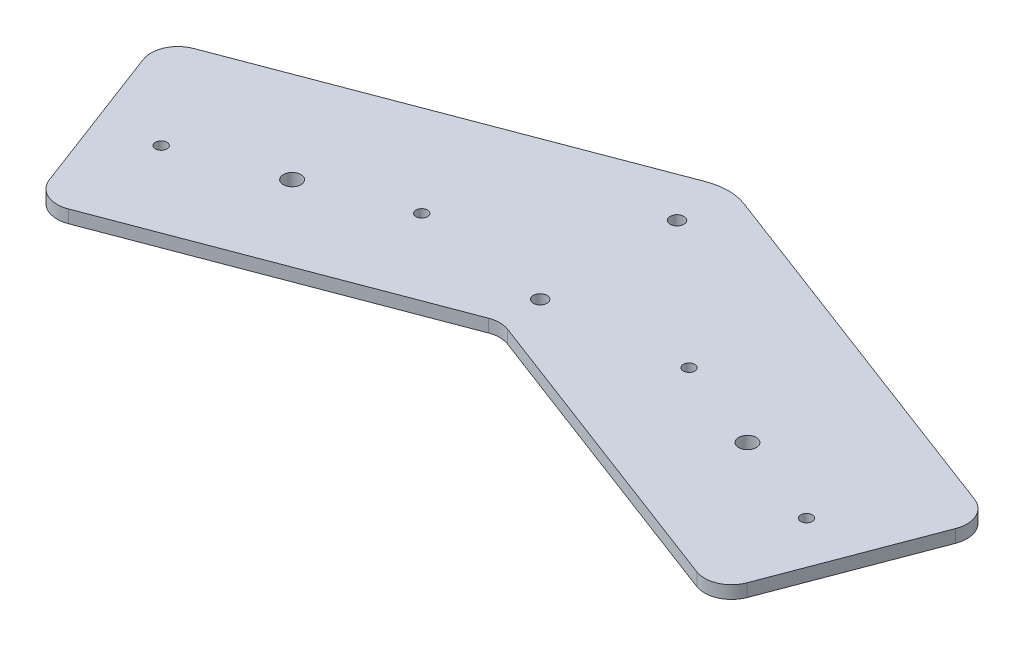
SolidWorks part; units mm, degrees
ref_plane "Front Plane" through (0, 0, 0) normal (0, 0, 1) x (1, 0, 0)
ref_plane "Top Plane" through (0, 0, 0) normal (0, 1, 0) x (1, 0, 0)
ref_plane "Right Plane" through (0, 0, 0) normal (1, 0, 0) x (0, 0, -1)
sketch "Sketch2" plane through (0, 0, 0) normal (0, 1, 0) x (1, 0, 0)
  line L2 (144.946, 76.6792) -> (7.086, 128.91)
  line L3 (-7.0857, 128.91) -> (-144.9459, 76.6798)
  line L6 (-100.0004, 93.708) -> (0.0002, 131.5946) construction
  line L7 (0.0002, 131.5946) -> (99.9996, 93.708) construction
  line L8 (99.9996, 93.708) -> (84.4992, 52.7958) construction
  line L9 (-100.0004, 93.708) -> (-84.5003, 52.7958) construction
  line L10 (-88.0432, 62.1471) -> (-76.354, 66.5757) construction
  line L11 (-88.0432, 62.1471) -> (-99.7324, 57.7185) construction
  line L12 (76.353, 66.5758) -> (88.0422, 62.1472) construction
  line L13 (88.0422, 62.1472) -> (99.7313, 57.7185) construction
  line L14 (0, 131.3692) -> (0, -60.0537) construction
  line L25 (-150.7544, 63.7855) -> (-129.497, 7.6773)
  line L26 (-116.6028, 1.8689) -> (-3.5429, 44.7032)
  line L27 (3.5429, 44.7031) -> (116.6026, 1.8684)
  line L28 (129.4969, 7.6768) -> (150.7544, 63.7849)
  arc A5 (116.6026, 1.8684) -> (129.4969, 7.6768) centre (120.1455, 11.2197) ccw
  arc A6 (144.946, 76.6792) -> (150.7544, 63.7849) centre (141.4031, 67.3278) cw
  arc A7 (-3.5429, 44.7032) -> (3.5429, 44.7031) centre (0, 35.3518) cw
  arc A8 (-129.497, 7.6773) -> (-116.6028, 1.8689) centre (-120.1457, 11.2202) ccw
  arc A9 (-144.9459, 76.6798) -> (-150.7544, 63.7855) centre (-141.403, 67.3284) ccw
  arc A10 (-7.0857, 128.91) -> (7.086, 128.91) centre (0.0001, 110.2073) cw
  point P5 (0.0888, 131.5193)
  point P18 (125.9539, -1.6745)
  point P21 (154.2974, 73.1362)
  point P24 (0, 46.0454)
  point P29 (0.0693, 131.6451)
  point P30 (0.0002, 131.5946)
  point P34 (-125.9541, -1.674)
  point P37 (-154.2973, 73.1369)
  dimension "D9" = 138.5
  dimension "D4" = 80
  dimension "D17" = 10
  dimension "D18" = 20
  dimension "D2" = 165
  dimension "D3" = 165
  dimension "D5" = 138.5
  dimension "D6" = 80
  dimension "D7" = 200
  dimension "D8" = 43.75
  dimension "D10" = 43.75
  dimension "D11" = 33.75
  dimension "D12" = 12.5
  dimension "D13" = 12.5
  dimension "D14" = 33.75
  dimension "D15" = 12.5
  dimension "D16" = 12.5
extrude "Boss-Extrude1" add sketch "Sketch2" against normal blind 4.7625 contours L3 A9 L25 A8 L26 A7 L27 A5 L28 A6 L2 A10
hole_wizard "1/4 Clearance Hole4" positions "Sketch11" profile "Sketch12" hole size "1/4" standard "ANSI Inch" end condition through all
sketch "Sketch11" plane through (0, 0, 0) normal (0, 1, 0) x (1, 0, 0)
  line L0 (144.946, 76.6792) -> (7.086, 128.91) construction
  line L1 (-7.0857, 128.91) -> (-144.9459, 76.6798) construction
  line L2 (-100, 93.7081) -> (100, 93.7078) construction
  line L3 (100, 93.7078) -> (84.4998, 52.7959) construction
  line L4 (84.4998, 52.7959) -> (-84.4999, 52.7959) construction
  line L5 (-84.4999, 52.7959) -> (-100, 93.7081) construction
  point P0 (84.4998, 52.7959)
  point P2 (-84.4999, 52.7959)
  point P27 (0, 0)
  point P28 (0, 0)
  dimension "D3" = 100
  dimension "D4" = 90
  dimension "D5" = 200
  dimension "D6" = 90
  dimension "D8" = 43.75
sketch "Sketch12" plane through (84.4998, 0, -52.7959) normal (1, 0, 0) x (0, 0, 1)
  line L0 (0, 0) -> (0, 4.7625)
  line L1 (0, 4.7625) -> (3.2639, 4.7625)
  line L2 (3.2639, 4.7625) -> (3.2639, 0)
  line L5 (3.2639, 0) -> (0, 0)
  line L11 (0, -6.35) -> (0, 107.95) construction
  dimension "Thru Hole Dia." = 6.5278
  dimension "Thru Hole Depth" = 4.7625
hole_wizard "M4 Clearance Hole1" positions "Sketch13" profile "Sketch14" hole size "M4" standard "ANSI Metric" end condition through all
sketch "Sketch13" plane through (0, 0, 0) normal (0, 1, 0) x (1, 0, 0)
  line L0 (-7.0857, 128.91) -> (-144.9459, 76.6798) construction
  line L1 (144.946, 76.6792) -> (7.086, 128.91) construction
  line L2 (-100, 93.7081) -> (100, 93.7078) construction
  line L9 (-100, 93.7081) -> (-84.6785, 52.7287) construction
  line L10 (-84.6785, 52.7287) -> (84.6785, 52.7287) construction
  line L11 (84.6785, 52.7287) -> (100, 93.7078) construction
  point P0 (-49.6108, 66.0141)
  point P2 (-119.7459, 39.4425)
  point P4 (49.6107, 66.014)
  point P6 (119.7458, 39.442)
  dimension "D1" = 200
  dimension "D2" = 37.5
  dimension "D3" = 43.75
  dimension "D4" = 43.75
  dimension "D5" = 43.75
  dimension "D6" = 43.75
  dimension "D7" = 100
  dimension "D8" = 69.5
  dimension "D9" = 69.5
  dimension "D10" = 43.75
  dimension "D11" = 37.5
  dimension "D12" = 37.5
  dimension "D13" = 37.5
sketch "Sketch14" plane through (-49.6108, 0, -66.0141) normal (1, 0, 0) x (0, 0, 1)
  line L0 (0, 0) -> (0, 4.7625)
  line L1 (0, 4.7625) -> (2.15, 4.7625)
  line L2 (2.15, 4.7625) -> (2.15, 0)
  line L5 (2.15, 0) -> (0, 0)
  line L11 (0, -6.35) -> (0, 107.95) construction
  dimension "Thru Hole Dia." = 4.3
  dimension "Thru Hole Depth" = 4.7625
hole_wizard "1/4-20 Tapped Hole1" positions "Sketch15" profile "Sketch16" tap size "1/4-20" standard "ANSI Inch" end condition through all
sketch "Sketch15" plane through (0, 0, 0) normal (0, 1, 0) x (1, 0, 0)
  arc A1 (3.5429, 44.7031) -> (-3.5429, 44.7032) centre (0, 35.3518) ccw construction
  point P0 (0, 111.1518)
  point P2 (0, 60.3518)
  dimension "D1" = 50.8
  dimension "D2" = 25
sketch "Sketch16" plane through (0, 0, -111.1518) normal (1, 0, 0) x (0, 0, 1)
  line L0 (0, 0) -> (0, 4.7625)
  line L1 (0, 4.7625) -> (2.5527, 4.7625)
  line L2 (2.5527, 4.7625) -> (2.5527, 0)
  line L5 (2.5527, 0) -> (0, 0)
  line L11 (0, -6.35) -> (0, 107.95) construction
  dimension "Thru Tap Drill Dia." = 5.1054
  dimension "Thru Tap Drill Depth" = 4.7625
cosmetic thread "Hole Thread1"
cosmetic thread "Hole Thread2"
